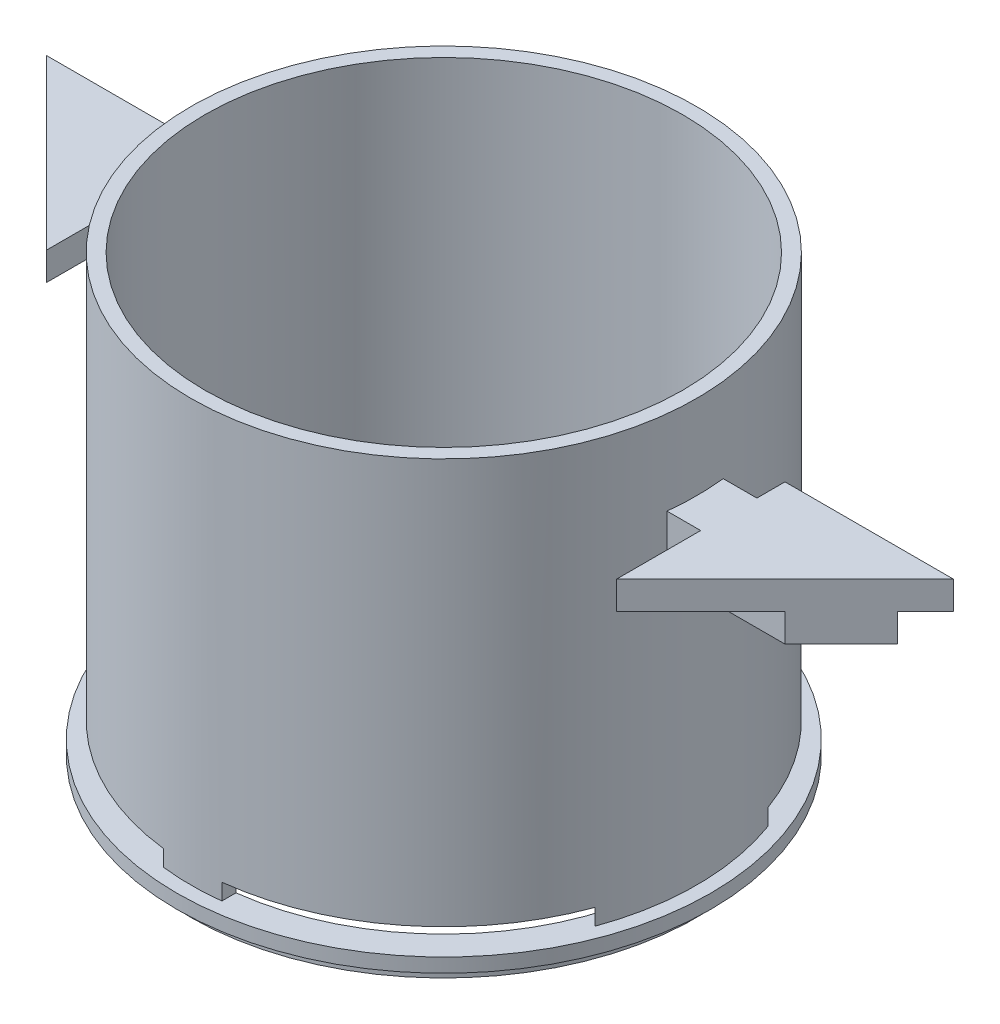
SolidWorks part; units mm, degrees
ref_plane "Front Plane" through (0, 0, 0) normal (0, 0, 1) x (1, 0, 0)
ref_plane "Top Plane" through (0, 0, 0) normal (0, 1, 0) x (1, 0, 0)
ref_plane "Right Plane" through (0, 0, 0) normal (1, 0, 0) x (0, 0, -1)
sketch "Sketch1" plane through (0, 0, 0) normal (0, 1, 0) x (1, 0, 0)
  circle A0 centre (0, 0) radius 57.15
  dimension "D2" = 114.3
extrude "Boss-Extrude1" add sketch "Sketch1" along normal blind 101.6
sketch "Sketch2" plane through (0, 101.6, 0) normal (0, 1, 0) x (1, 0, 0)
  circle A0 centre (0, 0) radius 53.975
  circle A1 centre (0, 0) radius 57.15 construction
  dimension "D2" = 3.175
extrude "Cut-Extrude1" cut sketch "Sketch2" against normal through all
sketch "Sketch6" plane through (0, 0, 0) normal (0, 0, 1) x (1, 0, 0)
  line L0 (-57.15, 101.6) -> (-57.15, 0) construction
  line L1 (-53.721, 10.033) -> (-6.604, 10.033)
  line L2 (-53.721, 10.033) -> (-53.721, 6.35)
  line L3 (-53.721, 6.35) -> (-6.604, 6.35)
  line L7 (-53.975, 0) -> (53.975, 0) construction
  line L8 (-6.604, 10.033) -> (-6.604, 6.35)
  line L9 (0, 0) -> (0, 21.9448) construction
  line L10 (6.604, 10.033) -> (6.604, 6.35)
  line L11 (53.721, 6.35) -> (6.604, 6.35)
  line L12 (53.721, 10.033) -> (6.604, 10.033)
  line L13 (53.721, 10.033) -> (53.721, 6.35)
  dimension "D2" = 3.429
  dimension "D3" = 3.683
  dimension "D4" = 6.35
  dimension "D1" = 6.604
extrude "Cut-Extrude4" cut sketch "Sketch6" against normal through all both and the other way through all
ref_plane "Plane1" through (0, 69.85, 0) normal (0, 1, 0) x (1, 0, 0)
sketch "Sketch10" plane through (0, 0, 0) normal (0, 1, 0) x (1, 0, 0)
  circle A0 centre (0, 0) radius 60.325
  circle A1 centre (0, 0) radius 57.15 construction
  circle A2 centre (0, 0) radius 57.15
  dimension "D1" = 120.65
extrude "Boss-Extrude7" add sketch "Sketch10" along normal blind 3.175 from offset 3.175
sketch "Sketch9" plane through (0, 69.85, 0) normal (0, 1, 0) x (1, 0, 0)
  line L1 (-83.4526, -6.35) -> (-53.6002, -6.35)
  line L3 (-96.1526, 6.35) -> (-53.6002, 6.35)
  line L7 (-96.1526, 6.35) -> (-83.4526, -6.35)
  circle A0 centre (0, 0) radius 53.975 construction
  arc A1 (-53.6002, 6.35) -> (-53.6002, -6.35) centre (0, 0) ccw
  point P0 (0, 0)
  point P1 (0, 0)
  point P2 (-89.8026, 0)
  point P4 (0, 0)
  dimension "D1" = 96.1526
  dimension "D2" = 45
  dimension "D4" = 12.7
extrude "Boss-Extrude6" add sketch "Sketch9" along normal blind 12.7
sketch "Sketch11" plane through (0, 82.55, 0) normal (0, 1, 0) x (1, 0, 0)
  line L0 (-64.4026, -25.4) -> (-64.4026, 12.7)
  line L1 (-64.4026, 12.7) -> (-102.5026, 12.7)
  line L2 (-102.5026, 12.7) -> (-64.4026, -25.4)
  line L3 (-96.1526, 6.35) -> (-83.4526, -6.35) construction
  line L4 (-56.7961, 6.35) -> (-96.1526, 6.35) construction
  line L5 (-83.4526, -6.35) -> (-56.7961, -6.35) construction
  point P2 (0, 0)
  dimension "D1" = 6.35
  dimension "D2" = 19.05
extrude "Boss-Extrude8" add sketch "Sketch11" against normal blind 6.35
mirror "Mirror1" about plane through (0, 0, 0) normal (1, 0, 0) of "Boss-Extrude6", "Boss-Extrude8"
equation "\"tightTol\" = 0.005in"
equation "\"normTol\"= 0.01in"
equation "\"looseTol\"= 0.02in"
equation "\"D2@Sketch6\"=\"normTol\"+0.125000in"
equation "\"D1@Sketch6\"=\"normTol\"+0.250000in"
equation "\"D3@Sketch6\"=\"looseTol\"+0.125000in"
